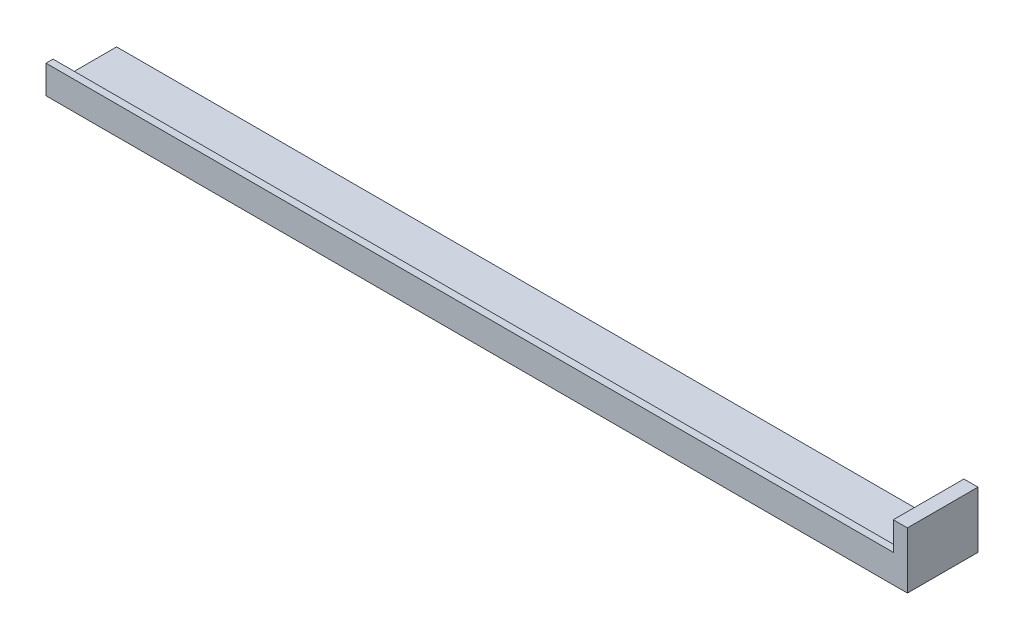
SolidWorks part; units mm, degrees
ref_plane "Ön Düzlem" through (0, 0, 0) normal (0, 0, 1) x (1, 0, 0)
ref_plane "Üst Düzlem" through (0, 0, 0) normal (0, 1, 0) x (1, 0, 0)
ref_plane "Sağ Düzlem" through (0, 0, 0) normal (1, 0, 0) x (0, 0, -1)
sketch "Çizim1" plane through (0, 0, 0) normal (0, 0, 1) x (1, 0, 0)
  line L0 (0, 0) -> (-120, 0)
  line L1 (0, 0) -> (0, 3)
  line L2 (0, 3) -> (2, 3)
  line L3 (2, 3) -> (2, -1)
  line L4 (2, -1) -> (-120, -1)
  line L5 (-120, 0) -> (-120, -1)
  dimension "D1" = 120
extrude "Yükseklik-Ekstrüzyon1" add sketch "Çizim1" along normal blind 10
sketch "Çizim2" plane through (0, 0, 0) normal (0, 1, 0) x (1, 0, 0)
  line L0 (0, -10) -> (0, 0) construction
  line L1 (-120, -10) -> (0, -10)
  line L2 (-120, -10) -> (-120, -9)
  line L3 (-120, -9) -> (0, -9)
  line L4 (0, -10) -> (0, -9)
  dimension "D1" = 1
extrude "Yükseklik-Ekstrüzyon2" add sketch "Çizim2" along normal up to surface (3 mm away) up to face at (1, 3, 5)
sketch "Çizim4" plane through (0, 3, 0) normal (0, 1, 0) x (1, 0, 0)
  line L1 (0, 0) -> (2, 0)
  line L2 (0, 0) -> (0, -10)
  line L3 (0, -10) -> (2, -10)
  line L4 (2, 0) -> (2, -10)
extrude "Yükseklik-Ekstrüzyon3" add sketch "Çizim4" along normal blind 4
